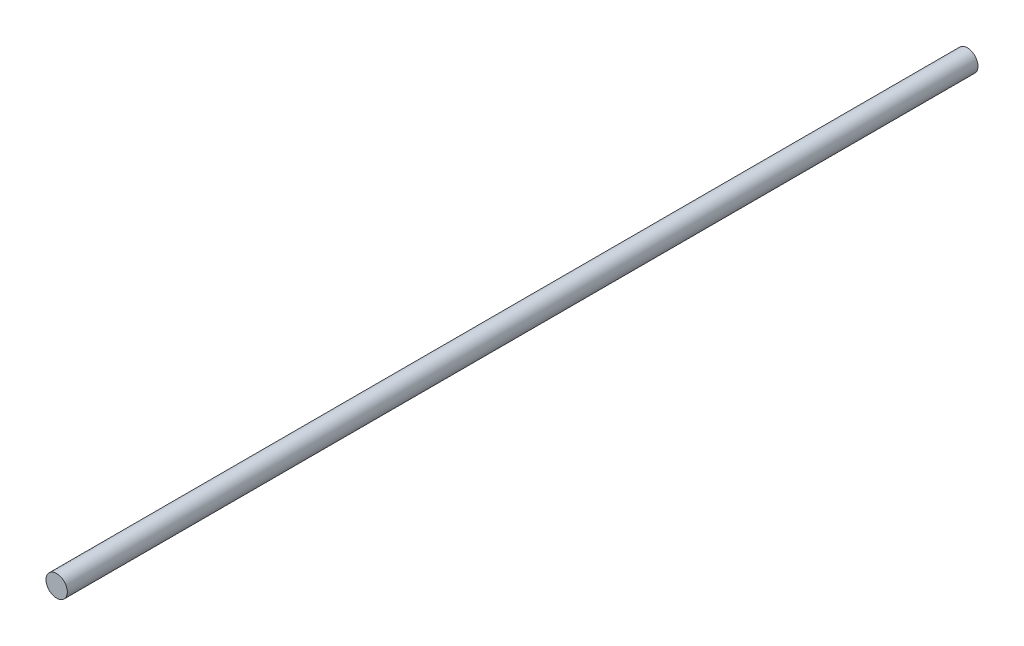
SolidWorks part; units mm, degrees
ref_plane "Front Plane" through (0, 0, 0) normal (0, 0, 1) x (1, 0, 0)
ref_plane "Top Plane" through (0, 0, 0) normal (0, 1, 0) x (1, 0, 0)
ref_plane "Right Plane" through (0, 0, 0) normal (1, 0, 0) x (0, 0, -1)
ref_plane "Plane1" through (0, 0, 200) normal (0, 0, 1) x (1, 0, 0)
ref_plane "Plane2" through (0, 0, 650) normal (0, 0, 1) x (1, 0, 0)
sketch "Sketch1" plane through (0, 0, 650) normal (0, 0, 1) x (1, 0, 0)
  line L0 (0, 109.7056) -> (0, 0) construction
  line L3 (78.3443, 73.2872) -> (-78.3443, 73.2872) construction
  circle A0 centre (0, 83.2872) radius 10
  spline S0 degree 3 poles (95, 99.9993) (95, 100.1689) (94.985, 100.3327) (94.9442, 100.5592) (94.9279, 100.6307) (94.8858, 100.7823) (94.8605, 100.8603) (94.7711, 101.0982) (94.6953, 101.2591) (94.4935, 101.6073) (94.37, 101.7895) (94.0685, 102.1714) (93.8894, 102.3722) (93.4864, 102.7759) (93.2639, 102.9777) (92.7778, 103.3797) (92.5142, 103.5798) (91.9503, 103.9768) (91.6515, 104.1727) (91.0327, 104.5527) (90.7111, 104.7379) (90.0453, 105.0996) (89.7002, 105.2767) (88.6431, 105.7923) (87.9085, 106.1152) (85.6292, 107.0349) (84.0288, 107.5758) (80.7447, 108.5514) (79.0596, 108.9861) (75.6446, 109.7754) (73.9138, 110.1299) (68.677, 111.1011) (65.1309, 111.6267) (57.9911, 112.5207) (54.395, 112.8882) (47.1781, 113.5116) (43.5566, 113.7666) (32.667, 114.4055) (25.379, 114.6647) (14.4303, 114.8958) (10.7775, 114.9459) (3.4683, 115.0012) (-0.1894, 115.007) (-11.1566, 114.9634) (-18.4613, 114.8506) (-29.3958, 114.4967) (-33.036, 114.3479) (-40.3036, 113.9709) (-43.9313, 113.7435) (-51.1631, 113.1855) (-54.7681, 112.8552) (-61.9373, 112.0522) (-65.5019, 111.5804) (-70.7841, 110.7134) (-72.534, 110.3975) (-75.9985, 109.6974) (-77.7141, 109.3132) (-81.0852, 108.4554) (-82.7417, 107.9818) (-85.1471, 107.1807) (-85.9329, 106.8992) (-87.4677, 106.3002) (-88.2144, 105.9838) (-89.6468, 105.3123) (-90.3356, 104.9562) (-91.292, 104.3973) (-91.5989, 104.2064) (-92.1876, 103.8143) (-92.4673, 103.6145) (-92.9849, 103.2141) (-93.2238, 103.0127) (-93.6595, 102.6093) (-93.8582, 102.4054) (-94.2016, 102.0114) (-94.3455, 101.8226) (-94.5845, 101.4611) (-94.6797, 101.2883) (-94.8258, 100.9667) (-94.8816, 100.8069) (-94.9391, 100.5827) (-94.954, 100.5109) (-94.9785, 100.3573) (-94.9877, 100.2775) (-94.9961, 100.1546) (-94.9991, 100.0925) (-95, 100.0268) (-95, 100.003) (-95, 99.9991) (-95, 99.994) (-95, 99.9868) (-95, 99.9689) (-95, 99.9222) (-95, 99.6494) (-95, 98.9315) (-95, 96.4047) (-95, 79.4057) (-95, 62.8662) (-95, 33.4625) (-95, 17.8419) (-95, 1.9915) (-95, 0.728) (-95, 0.3835) (-95, 0.1537) (-95, 0.0374) (-94.9997, -0.5145) (-94.9865, -2.7208) (-94.9124, -4.9201) (-94.6061, -10.1784) (-94.2309, -13.6581) (-93.0733, -20.5094) (-92.2908, -23.8805) (-90.2575, -30.4376) (-89.0071, -33.6212) (-86.0017, -39.7107) (-84.2485, -42.6117) (-81.2482, -46.691) (-80.1884, -48.0037) (-77.9514, -50.5304) (-76.7745, -51.745) (-74.316, -54.0684) (-73.0346, -55.1767) (-70.3742, -57.2887) (-68.9962, -58.292) (-64.7415, -61.1407) (-61.7404, -62.827) (-55.5033, -65.8035) (-52.266, -67.0957) (-45.6447, -69.3328) (-42.2571, -70.2781) (-35.3791, -71.8753) (-31.8912, -72.5281) (-24.8595, -73.5849) (-21.3129, -73.9887) (-14.1817, -74.5902) (-10.6005, -74.7874) (-5.2133, -74.9505) (-3.415, -74.9827) (0.1854, -75.0066) (1.9872, -74.9989) (7.3829, -74.9132) (10.9713, -74.772) (18.1202, -74.2916) (21.6814, -73.9534) (28.7476, -73.0417) (32.2538, -72.4676) (39.1884, -71.041) (42.6122, -70.189) (49.3209, -68.1542) (52.6088, -66.9709) (58.9802, -64.2249) (62.0605, -62.6615) (67.9222, -59.1147) (70.7044, -57.1297) (75.8666, -52.7366) (78.2486, -50.3244) (81.4616, -46.4169) (82.4744, -45.0646) (84.3762, -42.2733) (85.2643, -40.8354) (86.9158, -37.8795) (87.6794, -36.3621) (89.0817, -33.2636) (89.7203, -31.6821) (91.4572, -26.8546) (92.3743, -23.5302) (93.781, -16.7505) (94.2711, -13.2968) (94.7351, -8.0652) (94.8447, -6.313) (94.9471, -3.6763) (94.9829, -2.3558) (94.9976, -0.9224) (94.9995, -0.3707) (95, -0.15) (95, -0.0413) (95, 0.3033) (95, 4.2085) (95, 22.8155) (95, 41.1927) (95, 63.2455) (95, 70.5964) (95, 81.6227) (95, 87.1359) (95, 93.568) (95, 96.784) (95, 98.392) (95, 99.196) (95, 99.598) (95, 99.799) (95, 99.8995) (95, 99.9497) (95, 99.9749) (95, 99.9874) (95, 99.9928) (95, 99.9964) (95, 99.9993) (95, 100.1689) (94.985, 100.3327) knots -0.000008 -0.000008 0 0 0.001953 0.001953 0.00293 0.00293 0.003906 0.003906 0.005859 0.005859 0.007812 0.007812 0.009766 0.009766 0.011719 0.011719 0.013672 0.013672 0.015625 0.015625 0.017578 0.017578 0.019531 0.019531 0.023437 0.023437 0.03125 0.03125 0.039062 0.039062 0.046875 0.046875 0.0625 0.0625 0.078125 0.078125 0.09375 0.09375 0.125 0.125 0.140625 0.140625 0.15625 0.15625 0.1875 0.1875 0.203125 0.203125 0.21875 0.21875 0.234375 0.234375 0.25 0.25 0.257812 0.257812 0.265625 0.265625 0.273437 0.273437 0.277344 0.277344 0.28125 0.28125 0.285156 0.285156 0.287109 0.287109 0.289062 0.289062 0.291016 0.291016 0.292969 0.292969 0.294922 0.294922 0.296875 0.296875 0.298828 0.298828 0.299805 0.299805 0.300781 0.300781 0.30127 0.301514 0.301544 0.301544 0.301559 0.301559 0.301575 0.301636 0.301758 0.302734 0.304687 0.3125 0.375 0.375 0.4375 0.441406 0.442383 0.442871 0.442871 0.443359 0.443359 0.445312 0.453125 0.453125 0.46875 0.46875 0.484375 0.484375 0.5 0.5 0.515625 0.515625 0.523437 0.523437 0.53125 0.53125 0.539062 0.539062 0.546875 0.546875 0.5625 0.5625 0.578125 0.578125 0.59375 0.59375 0.609375 0.609375 0.625 0.625 0.640625 0.640625 0.648437 0.648437 0.65625 0.65625 0.671875 0.671875 0.6875 0.6875 0.703125 0.703125 0.71875 0.71875 0.734375 0.734375 0.75 0.75 0.765625 0.765625 0.78125 0.78125 0.789062 0.789062 0.796875 0.796875 0.804687 0.804687 0.8125 0.8125 0.828125 0.828125 0.84375 0.84375 0.851562 0.851562 0.855469 0.857422 0.85791 0.85791 0.858398 0.858398 0.859375 0.875 0.9375 0.9375 0.96875 0.96875 0.984375 0.992187 0.996094 0.998047 0.999023 0.999512 0.999756 0.999878 0.999939 0.999969 0.999985 0.999992 0.999992 1 1 1.001953 1.001953 1.00293 only from (95, 100) to (95, 100) construction
  point P6 (0, 83.2872)
  point P7 (0, 115.0002)
  point P10 (0, 93.2872)
  dimension "D1" = 20
  dimension "D3" = 73.2872
  dimension "D2" = 156.6885
extrude "Boss-Extrude1" add sketch "Sketch1" along normal blind 853
